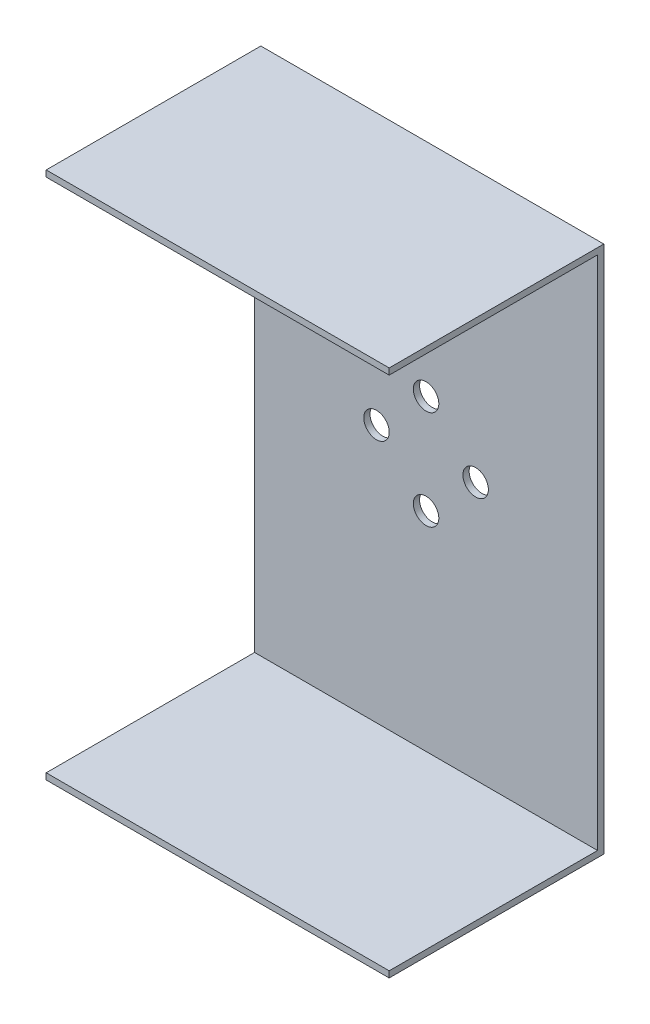
SolidWorks part; units mm, degrees
ref_plane "Front Plane" through (0, 0, 0) normal (0, 0, 1) x (1, 0, 0)
ref_plane "Top Plane" through (0, 0, 0) normal (0, 1, 0) x (1, 0, 0)
ref_plane "Right Plane" through (0, 0, 0) normal (1, 0, 0) x (0, 0, -1)
sketch "Sketch1" plane through (0, 0, 0) normal (1, 0, 0) x (0, 0, -1)
  line L0 (0, 0) -> (0, -1.6002)
  line L1 (0, -1.6002) -> (53.3998, -1.6002)
  line L2 (53.3998, -1.6002) -> (53.3998, -133.7877)
  line L3 (53.3998, -133.7877) -> (0, -133.7877)
  line L4 (0, -133.7877) -> (0, -135.3879)
  line L5 (0, -135.3879) -> (55, -135.3879)
  line L6 (55, -135.3879) -> (55, 0)
  line L7 (55, 0) -> (0, 0)
  line L8 (53.3998, -1.6002) -> (55, -1.6002) construction
  dimension "D1" = 135.3879
  dimension "D2" = 1.6002
  dimension "D3" = 55
extrude "Boss-Extrude1" add sketch "Sketch1" along normal blind 87.8907
sketch "Sketch2" plane through (0, 0, -53.3998) normal (0, 0, 1) x (1, 0, 0)
  line L0 (43.9453, -54.9939) -> (43.9453, -80.394) construction
  line L1 (31.2453, -67.694) -> (56.6453, -67.694) construction
  line L2 (0, -67.694) -> (87.8907, -67.6939) construction
  line L3 (0, -1.6002) -> (0, -133.7877) construction
  line L4 (87.8907, -1.6002) -> (87.8907, -133.7877) construction
  line L5 (43.9453, -1.6002) -> (43.9453, -133.7877) construction
  line L6 (87.8907, -1.6002) -> (0, -1.6002) construction
  line L7 (87.8907, -133.7877) -> (0, -133.7877) construction
  circle A0 centre (43.9453, -54.9939) radius 3.2639
  circle A1 centre (43.9453, -80.394) radius 3.2639
  circle A2 centre (31.2453, -67.694) radius 3.2639
  circle A3 centre (56.6453, -67.694) radius 3.2639
  point P9 (43.9453, -67.694)
  dimension "D1" = 6.5278
  dimension "D2" = 25.4
extrude "Cut-Extrude1" cut sketch "Sketch2" against normal up to surface (1.6002 mm away) up to face at (43.9453, -67.694, -55)
